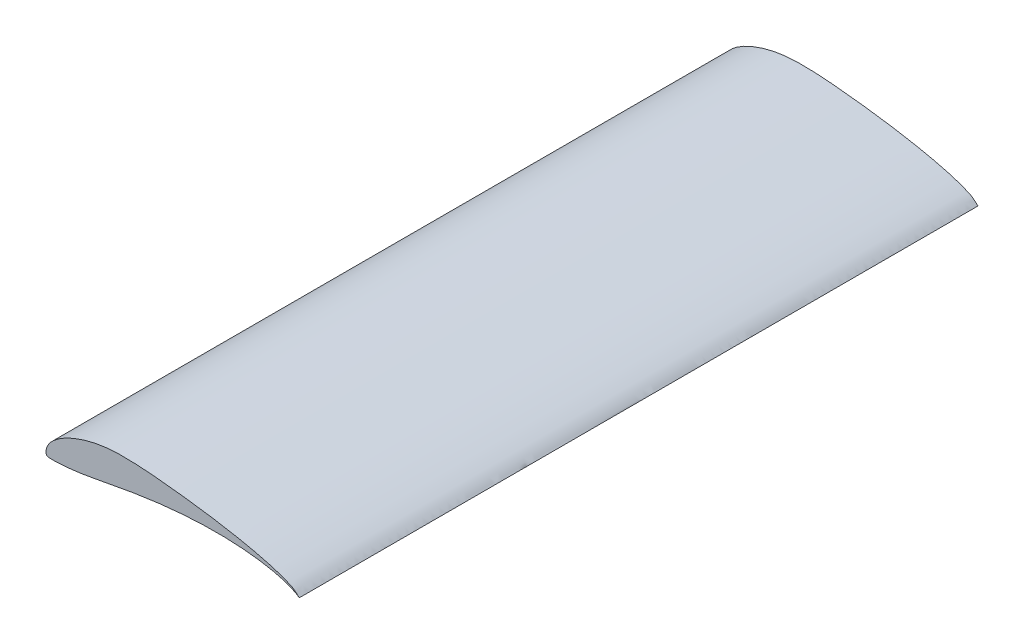
SolidWorks part; units mm, degrees
ref_plane "Front Plane" through (0, 0, 0) normal (0, 0, 1) x (1, 0, 0)
ref_plane "Top Plane" through (0, 0, 0) normal (0, 1, 0) x (1, 0, 0)
ref_plane "Right Plane" through (0, 0, 0) normal (1, 0, 0) x (0, 0, -1)
curve "Curve1"
  spline degree 3 poles (354.2239, 0.9234, 0) (355.9224, -0.2295, 0) (354.4331, 0.88, 0) (353.4445, 1.8501, 0) (351.2493, 3.8761, 0) (348.6595, 6.0315, 0) (345.1169, 8.2044, 0) (340.7116, 10.3101, 0) (335.3934, 12.5077, 0) (329.1704, 14.7666, 0) (322.0716, 17.0707, 0) (314.1338, 19.4002, 0) (305.4016, 21.744, 0) (295.9231, 24.0806, 0) (285.7526, 26.3932, 0) (274.9509, 28.6672, 0) (263.5838, 30.8911, 0) (251.7177, 33.0373, 0) (239.4275, 35.1029, 0) (226.7839, 37.0613, 0) (213.8688, 38.9163, 0) (200.7648, 40.6531, 0) (187.5669, 42.2663, 0) (174.3805, 43.7672, 0) (161.315, 45.118, 0) (148.4766, 46.2934, 0) (135.9557, 47.2272, 0) (123.8239, 47.8695, 0) (112.1485, 48.1469, 0) (100.9895, 48.1174, 0) (90.3676, 47.571, 0) (80.2788, 46.4638, 0) (70.6819, 44.8982, 0) (61.5746, 42.87, 0) (52.9664, 40.4916, 0) (44.8935, 37.8052, 0) (37.3904, 34.8735, 0) (30.5037, 31.7124, 0) (24.2554, 28.386, 0) (18.6796, 24.932, 0) (13.8112, 21.3974, 0) (9.6523, 17.857, 0) (6.263, 14.2722, 0) (3.6597, 10.674, 0) (1.7367, 7.1735, 0) (0.5042, 3.8499, 0) (-0.0831, 0.7822, 0) (0.0303, -1.8124, 0) (0.6983, -4.192, 0) (3.1812, -5.3732, 0) (6.5196, -5.539, 0) (11.0865, -5.6996, 0) (16.8297, -5.4519, 0) (23.6842, -4.9968, 0) (31.5739, -4.2678, 0) (40.4179, -3.2814, 0) (50.1732, -2.0165, 0) (60.835, -0.2486, 0) (72.4551, 1.9683, 0) (85.0918, 4.381, 0) (98.6831, 6.9285, 0) (113.1438, 9.505, 0) (128.3676, 12.0138, 0) (144.2365, 14.3712, 0) (160.6136, 16.4907, 0) (177.3518, 18.3106, 0) (194.2928, 19.7491, 0) (211.2668, 20.7688, 0) (228.0962, 21.3294, 0) (244.5987, 21.4002, 0) (260.59, 20.9764, 0) (275.8871, 20.0679, 0) (290.306, 18.6865, 0) (303.6751, 16.8851, 0) (315.8202, 14.7161, 0) (326.5991, 12.252, 0) (335.8129, 9.6154, 0) (343.3535, 6.8013, 0) (348.7336, 4.2261, 0) (352.7001, 1.8449, 0) (354.2239, 0.9234, 0) (355.9224, -0.2295, 0) (354.4331, 0.88, 0) knots -0.009748 -0.004147 -0.001 0 0.00098 0.003649 0.007483 0.012095 0.017526 0.024052 0.031783 0.040678 0.05071 0.061833 0.073989 0.087118 0.101145 0.115991 0.13157 0.147788 0.164551 0.181758 0.199312 0.217095 0.23499 0.252857 0.270541 0.287887 0.304773 0.321101 0.336806 0.3518 0.366031 0.379616 0.392653 0.40517 0.417172 0.428604 0.439419 0.449597 0.459102 0.467908 0.475988 0.483309 0.489875 0.495803 0.501149 0.505903 0.510047 0.513579 0.516447 0.51935 0.523823 0.529974 0.537716 0.546968 0.557637 0.56962 0.582804 0.597247 0.613135 0.630444 0.649056 0.668822 0.689595 0.71119 0.733427 0.756094 0.778989 0.80189 0.824567 0.846792 0.868338 0.888978 0.908492 0.926659 0.943286 0.958169 0.971136 0.981956 0.990252 0.995853 0.999 1 1.00098 1.003649 1.007483 periodic
sketch "Sketch1" plane through (0, 0, 0) normal (0, 0, 1) x (1, 0, 0)
  spline S0 degree 3 poles (354.2239, 0.9234) (355.9224, -0.2295) (354.4331, 0.88) (353.4445, 1.8501) (351.2493, 3.8761) (348.6595, 6.0315) (345.1169, 8.2044) (340.7116, 10.3101) (335.3934, 12.5077) (329.1704, 14.7666) (322.0716, 17.0707) (314.1338, 19.4002) (305.4016, 21.744) (295.9231, 24.0806) (285.7526, 26.3932) (274.9509, 28.6672) (263.5838, 30.8911) (251.7177, 33.0373) (239.4275, 35.1029) (226.7839, 37.0613) (213.8688, 38.9163) (200.7648, 40.6531) (187.5669, 42.2663) (174.3805, 43.7672) (161.315, 45.118) (148.4766, 46.2934) (135.9557, 47.2272) (123.8239, 47.8695) (112.1485, 48.1469) (100.9895, 48.1174) (90.3676, 47.571) (80.2788, 46.4638) (70.6819, 44.8982) (61.5746, 42.87) (52.9664, 40.4916) (44.8935, 37.8052) (37.3904, 34.8735) (30.5037, 31.7124) (24.2554, 28.386) (18.6796, 24.932) (13.8112, 21.3974) (9.6523, 17.857) (6.263, 14.2722) (3.6597, 10.674) (1.7367, 7.1735) (0.5042, 3.8499) (-0.0831, 0.7822) (0.0303, -1.8124) (0.6983, -4.192) (3.1812, -5.3732) (6.5196, -5.539) (11.0865, -5.6996) (16.8297, -5.4519) (23.6842, -4.9968) (31.5739, -4.2678) (40.4179, -3.2814) (50.1732, -2.0165) (60.835, -0.2486) (72.4551, 1.9683) (85.0918, 4.381) (98.6831, 6.9285) (113.1438, 9.505) (128.3676, 12.0138) (144.2365, 14.3712) (160.6136, 16.4907) (177.3518, 18.3106) (194.2928, 19.7491) (211.2668, 20.7688) (228.0962, 21.3294) (244.5987, 21.4002) (260.59, 20.9764) (275.8871, 20.0679) (290.306, 18.6865) (303.6751, 16.8851) (315.8202, 14.7161) (326.5991, 12.252) (335.8129, 9.6154) (343.3535, 6.8013) (348.7336, 4.2261) (352.7001, 1.8449) (354.2239, 0.9234) (355.9224, -0.2295) (354.4331, 0.88) knots -0.009748 -0.004147 -0.001 0 0.00098 0.003649 0.007483 0.012095 0.017526 0.024052 0.031783 0.040678 0.05071 0.061833 0.073989 0.087118 0.101145 0.115991 0.13157 0.147788 0.164551 0.181758 0.199312 0.217095 0.23499 0.252857 0.270541 0.287887 0.304773 0.321101 0.336806 0.3518 0.366031 0.379616 0.392653 0.40517 0.417172 0.428604 0.439419 0.449597 0.459102 0.467908 0.475988 0.483309 0.489875 0.495803 0.501149 0.505903 0.510047 0.513579 0.516447 0.51935 0.523823 0.529974 0.537716 0.546968 0.557637 0.56962 0.582804 0.597247 0.613135 0.630444 0.649056 0.668822 0.689595 0.71119 0.733427 0.756094 0.778989 0.80189 0.824567 0.846792 0.868338 0.888978 0.908492 0.926659 0.943286 0.958169 0.971136 0.981956 0.990252 0.995853 0.999 1 1.00098 1.003649 1.007483 only from (355.6, 0) to (355.6, 0) construction
  spline S1 degree 3 poles (354.2239, 0.9234) (355.9224, -0.2295) (354.4331, 0.88) (353.4445, 1.8501) (351.2493, 3.8761) (348.6595, 6.0315) (345.1169, 8.2044) (340.7116, 10.3101) (335.3934, 12.5077) (329.1704, 14.7666) (322.0716, 17.0707) (314.1338, 19.4002) (305.4016, 21.744) (295.9231, 24.0806) (285.7526, 26.3932) (274.9509, 28.6672) (263.5838, 30.8911) (251.7177, 33.0373) (239.4275, 35.1029) (226.7839, 37.0613) (213.8688, 38.9163) (200.7648, 40.6531) (187.5669, 42.2663) (174.3805, 43.7672) (161.315, 45.118) (148.4766, 46.2934) (135.9557, 47.2272) (123.8239, 47.8695) (112.1485, 48.1469) (100.9895, 48.1174) (90.3676, 47.571) (80.2788, 46.4638) (70.6819, 44.8982) (61.5746, 42.87) (52.9664, 40.4916) (44.8935, 37.8052) (37.3904, 34.8735) (30.5037, 31.7124) (24.2554, 28.386) (18.6796, 24.932) (13.8112, 21.3974) (9.6523, 17.857) (6.263, 14.2722) (3.6597, 10.674) (1.7367, 7.1735) (0.5042, 3.8499) (-0.0831, 0.7822) (0.0303, -1.8124) (0.6983, -4.192) (3.1812, -5.3732) (6.5196, -5.539) (11.0865, -5.6996) (16.8297, -5.4519) (23.6842, -4.9968) (31.5739, -4.2678) (40.4179, -3.2814) (50.1732, -2.0165) (60.835, -0.2486) (72.4551, 1.9683) (85.0918, 4.381) (98.6831, 6.9285) (113.1438, 9.505) (128.3676, 12.0138) (144.2365, 14.3712) (160.6136, 16.4907) (177.3518, 18.3106) (194.2928, 19.7491) (211.2668, 20.7688) (228.0962, 21.3294) (244.5987, 21.4002) (260.59, 20.9764) (275.8871, 20.0679) (290.306, 18.6865) (303.6751, 16.8851) (315.8202, 14.7161) (326.5991, 12.252) (335.8129, 9.6154) (343.3535, 6.8013) (348.7336, 4.2261) (352.7001, 1.8449) (354.2239, 0.9234) (355.9224, -0.2295) (354.4331, 0.88) knots -0.009748 -0.004147 -0.001 0 0.00098 0.003649 0.007483 0.012095 0.017526 0.024052 0.031783 0.040678 0.05071 0.061833 0.073989 0.087118 0.101145 0.115991 0.13157 0.147788 0.164551 0.181758 0.199312 0.217095 0.23499 0.252857 0.270541 0.287887 0.304773 0.321101 0.336806 0.3518 0.366031 0.379616 0.392653 0.40517 0.417172 0.428604 0.439419 0.449597 0.459102 0.467908 0.475988 0.483309 0.489875 0.495803 0.501149 0.505903 0.510047 0.513579 0.516447 0.51935 0.523823 0.529974 0.537716 0.546968 0.557637 0.56962 0.582804 0.597247 0.613135 0.630444 0.649056 0.668822 0.689595 0.71119 0.733427 0.756094 0.778989 0.80189 0.824567 0.846792 0.868338 0.888978 0.908492 0.926659 0.943286 0.958169 0.971136 0.981956 0.990252 0.995853 0.999 1 1.00098 1.003649 1.007483 only from (355.6, 0) to (355.6, 0)
extrude "Boss-Extrude1" add sketch "Sketch1" along normal blind 952.5
sketch "Sketch2" plane through (0, 0, 952.5) normal (0, 0, 1) x (1, 0, 0)
  line L0 (0, 0) -> (0, 65.688) construction
  line L1 (0, 0) -> (355.6, 0) construction
  line L2 (355.6, 0) -> (355.6, 65.688) construction
  spline S0 degree 3 poles (354.2239, 0.9234) (355.9224, -0.2295) (354.4331, 0.88) (353.4445, 1.8501) (351.2493, 3.8761) (348.6595, 6.0315) (345.1169, 8.2044) (340.7116, 10.3101) (335.3934, 12.5077) (329.1704, 14.7666) (322.0716, 17.0707) (314.1338, 19.4002) (305.4016, 21.744) (295.9231, 24.0806) (285.7526, 26.3932) (274.9509, 28.6672) (263.5838, 30.8911) (251.7177, 33.0373) (239.4275, 35.1029) (226.7839, 37.0613) (213.8688, 38.9163) (200.7648, 40.6531) (187.5669, 42.2663) (174.3805, 43.7672) (161.315, 45.118) (148.4766, 46.2934) (135.9557, 47.2272) (123.8239, 47.8695) (112.1485, 48.1469) (100.9895, 48.1174) (90.3676, 47.571) (80.2788, 46.4638) (70.6819, 44.8982) (61.5746, 42.87) (52.9664, 40.4916) (44.8935, 37.8052) (37.3904, 34.8735) (30.5037, 31.7124) (24.2554, 28.386) (18.6796, 24.932) (13.8112, 21.3974) (9.6523, 17.857) (6.263, 14.2722) (3.6597, 10.674) (1.7367, 7.1735) (0.5042, 3.8499) (-0.0831, 0.7822) (0.0303, -1.8124) (0.6983, -4.192) (3.1812, -5.3732) (6.5196, -5.539) (11.0865, -5.6996) (16.8297, -5.4519) (23.6842, -4.9968) (31.5739, -4.2678) (40.4179, -3.2814) (50.1732, -2.0165) (60.835, -0.2486) (72.4551, 1.9683) (85.0918, 4.381) (98.6831, 6.9285) (113.1438, 9.505) (128.3676, 12.0138) (144.2365, 14.3712) (160.6136, 16.4907) (177.3518, 18.3106) (194.2928, 19.7491) (211.2668, 20.7688) (228.0962, 21.3294) (244.5987, 21.4002) (260.59, 20.9764) (275.8871, 20.0679) (290.306, 18.6865) (303.6751, 16.8851) (315.8202, 14.7161) (326.5991, 12.252) (335.8129, 9.6154) (343.3535, 6.8013) (348.7336, 4.2261) (352.7001, 1.8449) (354.2239, 0.9234) (355.9224, -0.2295) (354.4331, 0.88) knots -0.009748 -0.004147 -0.001 0 0.00098 0.003649 0.007483 0.012095 0.017526 0.024052 0.031783 0.040678 0.05071 0.061833 0.073989 0.087118 0.101145 0.115991 0.13157 0.147788 0.164551 0.181758 0.199312 0.217095 0.23499 0.252857 0.270541 0.287887 0.304773 0.321101 0.336806 0.3518 0.366031 0.379616 0.392653 0.40517 0.417172 0.428604 0.439419 0.449597 0.459102 0.467908 0.475988 0.483309 0.489875 0.495803 0.501149 0.505903 0.510047 0.513579 0.516447 0.51935 0.523823 0.529974 0.537716 0.546968 0.557637 0.56962 0.582804 0.597247 0.613135 0.630444 0.649056 0.668822 0.689595 0.71119 0.733427 0.756094 0.778989 0.80189 0.824567 0.846792 0.868338 0.888978 0.908492 0.926659 0.943286 0.958169 0.971136 0.981956 0.990252 0.995853 0.999 1 1.00098 1.003649 1.007483 only from (355.6, 0) to (355.6, 0) construction
  spline S1 degree 3 poles (354.2239, 0.9234) (355.9224, -0.2295) (354.4331, 0.88) (353.4445, 1.8501) (351.2493, 3.8761) (348.6595, 6.0315) (345.1169, 8.2044) (340.7116, 10.3101) (335.3934, 12.5077) (329.1704, 14.7666) (322.0716, 17.0707) (314.1338, 19.4002) (305.4016, 21.744) (295.9231, 24.0806) (285.7526, 26.3932) (274.9509, 28.6672) (263.5838, 30.8911) (251.7177, 33.0373) (239.4275, 35.1029) (226.7839, 37.0613) (213.8688, 38.9163) (200.7648, 40.6531) (187.5669, 42.2663) (174.3805, 43.7672) (161.315, 45.118) (148.4766, 46.2934) (135.9557, 47.2272) (123.8239, 47.8695) (112.1485, 48.1469) (100.9895, 48.1174) (90.3676, 47.571) (80.2788, 46.4638) (70.6819, 44.8982) (61.5746, 42.87) (52.9664, 40.4916) (44.8935, 37.8052) (37.3904, 34.8735) (30.5037, 31.7124) (24.2554, 28.386) (18.6796, 24.932) (13.8112, 21.3974) (9.6523, 17.857) (6.263, 14.2722) (3.6597, 10.674) (1.7367, 7.1735) (0.5042, 3.8499) (-0.0831, 0.7822) (0.0303, -1.8124) (0.6983, -4.192) (3.1812, -5.3732) (6.5196, -5.539) (11.0865, -5.6996) (16.8297, -5.4519) (23.6842, -4.9968) (31.5739, -4.2678) (40.4179, -3.2814) (50.1732, -2.0165) (60.835, -0.2486) (72.4551, 1.9683) (85.0918, 4.381) (98.6831, 6.9285) (113.1438, 9.505) (128.3676, 12.0138) (144.2365, 14.3712) (160.6136, 16.4907) (177.3518, 18.3106) (194.2928, 19.7491) (211.2668, 20.7688) (228.0962, 21.3294) (244.5987, 21.4002) (260.59, 20.9764) (275.8871, 20.0679) (290.306, 18.6865) (303.6751, 16.8851) (315.8202, 14.7161) (326.5991, 12.252) (335.8129, 9.6154) (343.3535, 6.8013) (348.7336, 4.2261) (352.7001, 1.8449) (354.2239, 0.9234) (355.9224, -0.2295) (354.4331, 0.88) knots -0.009748 -0.004147 -0.001 0 0.00098 0.003649 0.007483 0.012095 0.017526 0.024052 0.031783 0.040678 0.05071 0.061833 0.073989 0.087118 0.101145 0.115991 0.13157 0.147788 0.164551 0.181758 0.199312 0.217095 0.23499 0.252857 0.270541 0.287887 0.304773 0.321101 0.336806 0.3518 0.366031 0.379616 0.392653 0.40517 0.417172 0.428604 0.439419 0.449597 0.459102 0.467908 0.475988 0.483309 0.489875 0.495803 0.501149 0.505903 0.510047 0.513579 0.516447 0.51935 0.523823 0.529974 0.537716 0.546968 0.557637 0.56962 0.582804 0.597247 0.613135 0.630444 0.649056 0.668822 0.689595 0.71119 0.733427 0.756094 0.778989 0.80189 0.824567 0.846792 0.868338 0.888978 0.908492 0.926659 0.943286 0.958169 0.971136 0.981956 0.990252 0.995853 0.999 1 1.00098 1.003649 1.007483 only from (355.6, 0) to (355.6, 0) construction
sketch "Sketch3" plane through (0, 0, 0) normal (0, 0, -1) x (-1, 0, 0)
  line L0 (0, 0) -> (0, 65.688) construction
  line L1 (0, 0) -> (-355.6, 0) construction
  line L2 (-355.6, 0) -> (-355.6, 65.688) construction
  line L3 (0, 0) -> (0, 65.688) construction
  line L4 (0, 0) -> (-355.6, 0) construction
  line L5 (-355.6, 0) -> (-355.6, 65.688) construction
sketch3d "3DSketch1"
  line L0 (0, 0, 952.5) -> (0, 0, 0) construction
ref_plane "Plane1" through (0, 0, 476.25) normal (0, 0, -1) x (-1, 0, 0)
